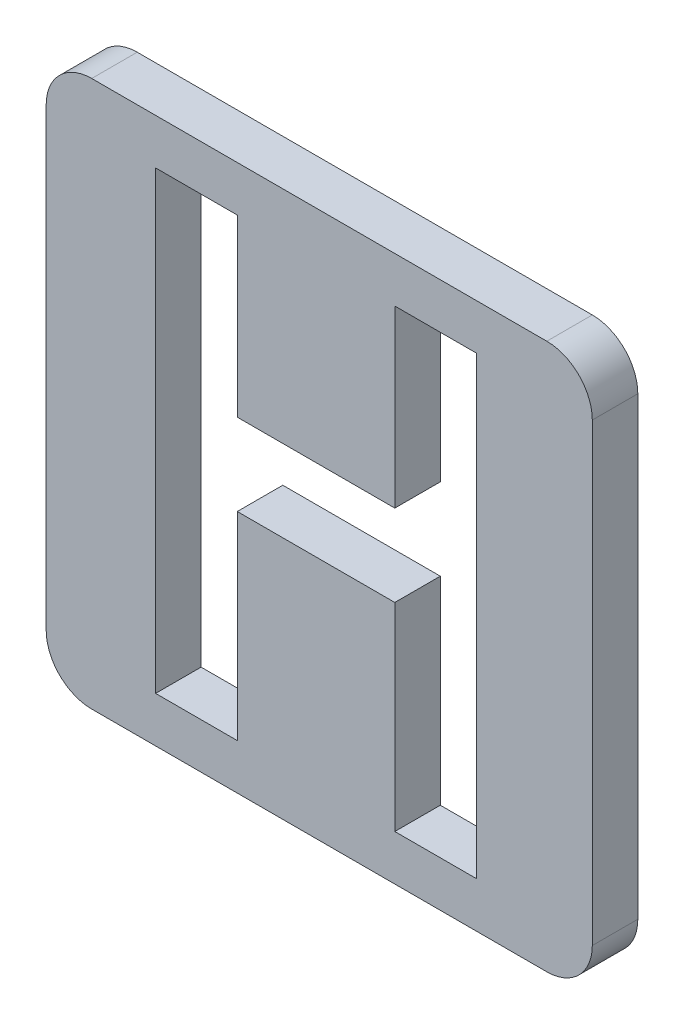
SolidWorks part; units mm, degrees
ref_plane "Front Plane" through (0, 0, 0) normal (0, 0, 1) x (1, 0, 0)
ref_plane "Top Plane" through (0, 0, 0) normal (0, 1, 0) x (1, 0, 0)
ref_plane "Right Plane" through (0, 0, 0) normal (1, 0, 0) x (0, 0, -1)
sketch "Sketch1" plane through (0, 0, 0) normal (0, 0, 1) x (1, 0, 0)
  line L1 (-50, 60) -> (50, 60)
  line L2 (-60, 50) -> (-60, -50)
  line L3 (-50, -60) -> (50, -60)
  line L4 (60, 50) -> (60, -50)
  line L5 (-60, 60) -> (60, -60) construction
  line L6 (-60, -60) -> (60, 60) construction
  arc A0 (-60, -50) -> (-50, -60) centre (-50, -50) ccw
  arc A1 (50, -60) -> (60, -50) centre (50, -50) ccw
  arc A2 (50, 60) -> (60, 50) centre (50, 50) cw
  arc A3 (-50, 60) -> (-60, 50) centre (-50, 50) ccw
  point P0 (0, 0)
  dimension "D3" = 10
  dimension "D1" = 120
  dimension "D2" = 120
extrude "Boss-Extrude1" add sketch "Sketch1" along normal blind 10 contours A3 L2 A0 L3 A1 L4 A2 L1
sketch "Sketch2" plane through (0, 0, 10) normal (0, 0, 1) x (1, 0, 0)
  line L0 (0, 0) -> (0, 40) construction
  line L1 (-50, 50) -> (50, 50) construction
  line L2 (-50, 50) -> (-50, -50) construction
  line L3 (-50, -50) -> (50, -50) construction
  line L4 (50, 50) -> (50, -50) construction
  line L5 (-50, 50) -> (50, -50) construction
  line L6 (-50, -50) -> (50, 50) construction
  line L7 (0, 40) -> (-40, 40) construction
  line L8 (-40, 40) -> (-40, 0) construction
  line L9 (-40, 0) -> (0, 0) construction
  line L11 (0, 20) -> (-20, 20) construction
  line L12 (-20, 40) -> (-20, 20) construction
  circle A0 centre (0, 40) radius 4 construction
  circle A1 centre (0, 20) radius 4 construction
  circle A2 centre (0, 0) radius 4 construction
  circle A3 centre (-20, 20) radius 4 construction
  circle A4 centre (-20, 40) radius 4 construction
  circle A5 centre (-40, 40) radius 4 construction
  circle A6 centre (0, 0) radius 4 construction
  circle A7 centre (20, 0) radius 4 construction
  circle A8 centre (40, 0) radius 4 construction
  circle A9 centre (40, 20) radius 4 construction
  circle A10 centre (40, 40) radius 4 construction
  circle A11 centre (20, 20) radius 4 construction
  circle A12 centre (0, 0) radius 4 construction
  circle A13 centre (0, -20) radius 4 construction
  circle A14 centre (0, -40) radius 4 construction
  circle A15 centre (20, -40) radius 4 construction
  circle A16 centre (40, -40) radius 4 construction
  circle A17 centre (20, -20) radius 4 construction
  circle A18 centre (0, 0) radius 4 construction
  circle A19 centre (-20, 0) radius 4 construction
  circle A20 centre (-40, 0) radius 4 construction
  circle A21 centre (-40, -20) radius 4 construction
  circle A22 centre (-40, -40) radius 4 construction
  circle A23 centre (-20, -20) radius 4 construction
  text T0 "H" font "Century Gothic" height 100
  point P0 (0, 0)
  point P55 (0, 0)
  dimension "D4" = 8
  dimension "D1" = 100
  dimension "D2" = 100
  dimension "D3" = 40
  dimension "D5" = 4
extrude "Cut-Extrude21" cut sketch "Sketch2" against normal blind 10
